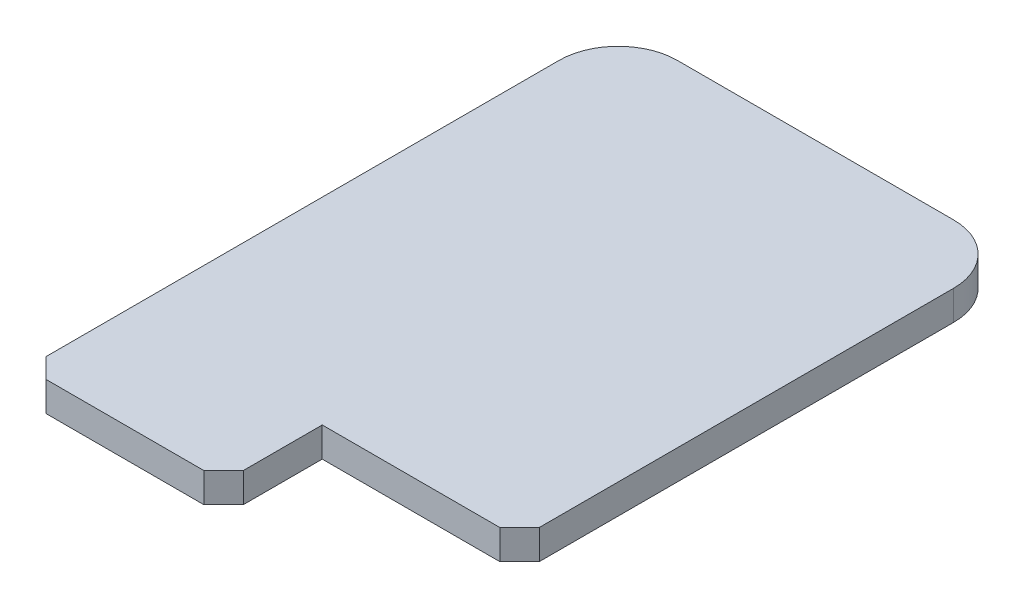
SolidWorks part; units mm, degrees
ref_plane "Front Plane" through (0, 0, 0) normal (0, 0, 1) x (1, 0, 0)
ref_plane "Top Plane" through (0, 0, 0) normal (0, 1, 0) x (1, 0, 0)
ref_plane "Right Plane" through (0, 0, 0) normal (1, 0, 0) x (0, 0, -1)
sketch "Sketch1" plane through (0, 0, 0) normal (0, 1, 0) x (1, 0, 0)
  line L0 (0, 0) -> (0, 5)
  line L1 (0, 5) -> (10, 5)
  line L2 (10, 5) -> (10, 30)
  line L3 (10, 30) -> (-10, 30)
  line L4 (-10, 30) -> (-10, 0)
  line L5 (-10, 0) -> (0, 0)
  point P3 (0.1896, 0)
  dimension "D1" = 20
  dimension "D2" = 30
  dimension "D3" = 5
extrude "Boss-Extrude1" add sketch "Sketch1" along normal blind 1.5
fillet "Fillet1" radius 3 2 edges at (10, 0.75, -30) (-10, 0.75, -30)
chamfer "Chamfer1" distance 1 angle 45 3 edges at (10, 0.75, -5) (0, 0.75, 0) (-10, 0.75, 0)
